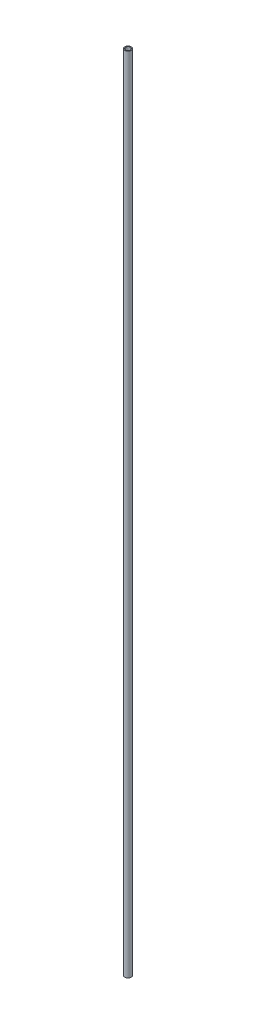
SolidWorks part; units mm, degrees
ref_plane "Front Plane" through (0, 0, 0) normal (0, 0, 1) x (1, 0, 0)
ref_plane "Top Plane" through (0, 0, 0) normal (0, 1, 0) x (1, 0, 0)
ref_plane "Right Plane" through (0, 0, 0) normal (1, 0, 0) x (0, 0, -1)
sketch "Sketch1" plane through (0, 0, 0) normal (0, 0, 1) x (1, 0, 0)
  line L0 (0, 0) -> (0, 1000)
  point P6 (0, 1000)
  dimension "D1" = 1000
sketch "Sketch2" plane through (0, 0, 0) normal (0, 1, 0) x (1, 0, 0)
  circle A0 centre (0, 0) radius 4
  circle A1 centre (0, 0) radius 3
  dimension "D1" = 6
  dimension "D2" = 8
sweep "Sweep1" add profiles "Sketch2" path "Sketch1"
